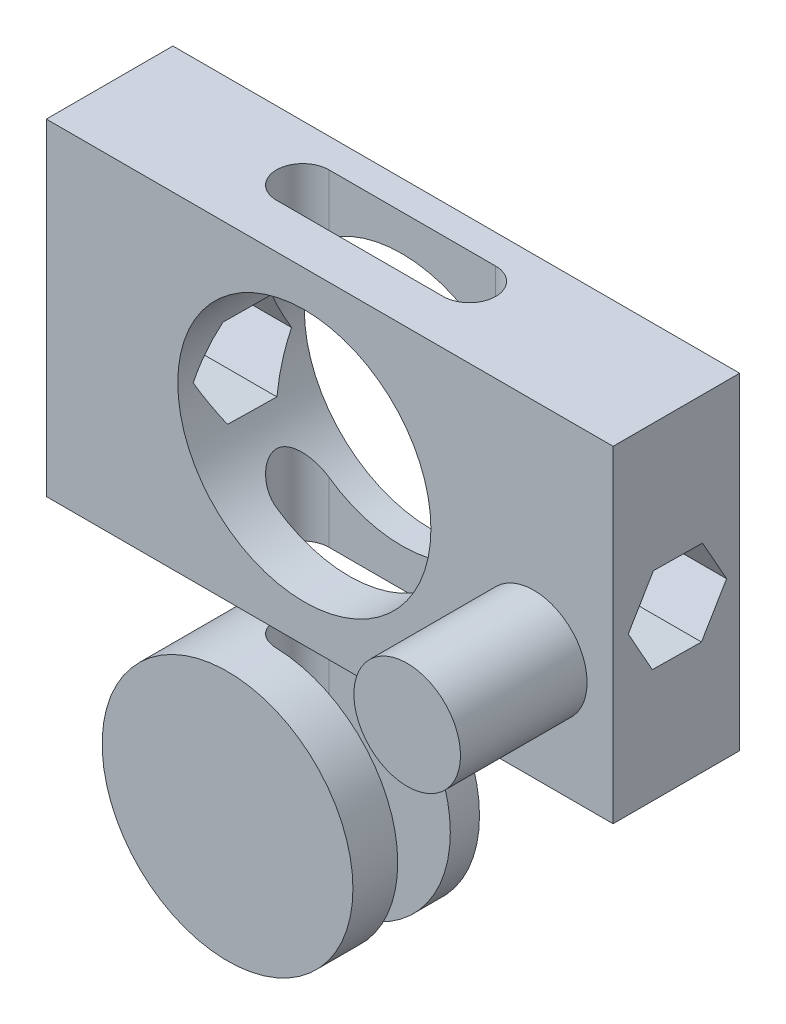
SolidWorks part; units mm, degrees
ref_plane "Front Plane" through (0, 0, 0) normal (0, 0, 1) x (1, 0, 0)
ref_plane "Top Plane" through (0, 0, 0) normal (0, 1, 0) x (1, 0, 0)
ref_plane "Right Plane" through (0, 0, 0) normal (1, 0, 0) x (0, 0, -1)
sketch "Sketch1" plane through (0, 0, 0) normal (0, 0, 1) x (1, 0, 0)
  line L1 (-103.5509, 65.2821) -> (123.9181, 65.2821)
  line L2 (-103.5509, 65.2821) -> (-103.5509, -65.9253)
  line L3 (-103.5509, -65.9253) -> (123.9181, -65.9253)
  line L4 (123.9181, 65.2821) -> (123.9181, -65.9253)
  circle A0 centre (0, 0) radius 50.8
  circle A1 centre (-30.8228, -140.6864) radius 50.3263
  point P9 (57.454, -123.3114)
  point P10 (-30.8228, -140.6864)
  dimension "D1" = 101.6
extrude "Boss-Extrude1" add sketch "Sketch1" along normal blind 50.8
sketch "Sketch3" plane through (123.9181, 0, 0) normal (1, 0, 0) x (0, 0, -1)
  line L1 (-15.3295, -20.4833) -> (-5.2471, -3.5193)
  line L2 (-5.2471, -3.5193) -> (-14.8972, 13.6943)
  line L3 (-14.8972, 13.6943) -> (-34.6296, 13.9439)
  line L4 (-34.6296, 13.9439) -> (-44.712, -3.0201)
  line L5 (-44.712, -3.0201) -> (-35.062, -20.2337)
  line L6 (-35.062, -20.2337) -> (-15.3295, -20.4833)
  circle A0 centre (-24.9796, -3.2697) radius 17.0902 construction
extrude "Cut-Extrude1" cut sketch "Sketch3" against normal through all
sketch "Sketch2" plane through (0, 0, 50.8) normal (0, 0, 1) x (1, 0, 0)
  circle A0 centre (92.0786, -22.0482) radius 21.3961
extrude "Boss-Extrude2" add sketch "Sketch2" along normal blind 50.8
sketch "Sketch4" plane through (0, 65.2821, 0) normal (0, 1, 0) x (1, 0, 0)
  line L0 (-29.1677, -22.2703) -> (37.7295, -22.2703) construction
  line L1 (-29.1677, -11.717) -> (37.7295, -11.717)
  line L2 (-29.1677, -32.8236) -> (37.7295, -32.8236)
  arc A0 (-29.1677, -11.717) -> (-29.1677, -32.8236) centre (-29.1677, -22.2703) ccw
  arc A1 (37.7295, -32.8236) -> (37.7295, -11.717) centre (37.7295, -22.2703) ccw
  point P2 (4.2809, -22.2703)
extrude "Cut-Extrude2" cut sketch "Sketch4" against normal through all
